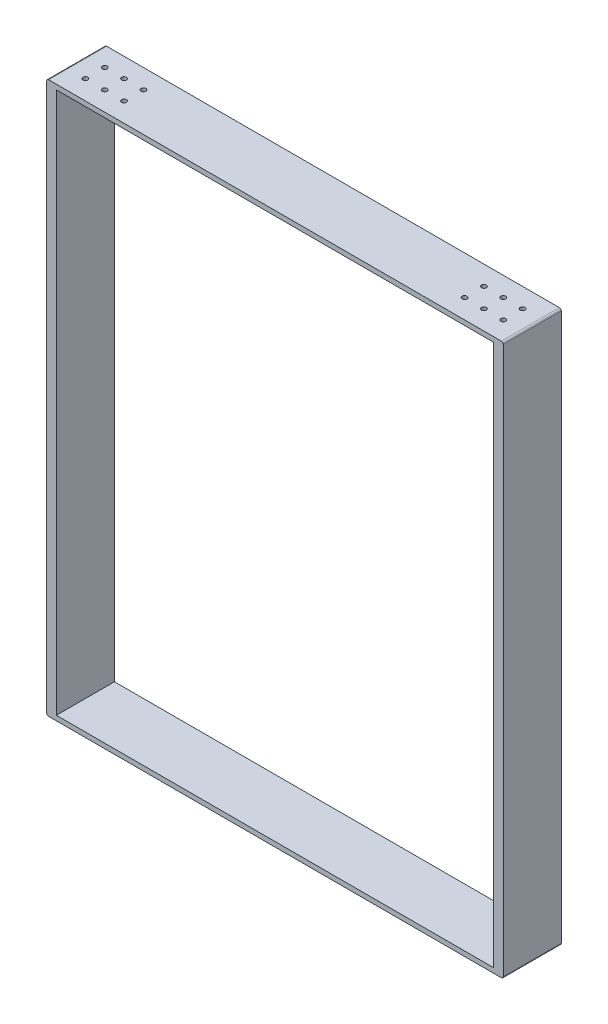
SolidWorks part; units mm, degrees
ref_plane "Front Plane" through (0, 0, 0) normal (0, 0, 1) x (1, 0, 0)
ref_plane "Top Plane" through (0, 0, 0) normal (0, 1, 0) x (1, 0, 0)
ref_plane "Right Plane" through (0, 0, 0) normal (1, 0, 0) x (0, 0, -1)
sketch "Sketch1" plane through (0, 0, 0) normal (0, 0, 1) x (1, 0, 0)
  line L0 (-287.02, 355.6) -> (-287.02, -355.6)
  line L1 (-287.02, -355.6) -> (287.02, -355.6)
  line L2 (287.02, -355.6) -> (287.02, 355.6)
  line L3 (287.02, 355.6) -> (-287.02, 355.6)
  line L4 (-299.72, 361.95) -> (-299.72, -361.95)
  line L5 (-299.72, -361.95) -> (299.72, -361.95)
  line L6 (299.72, -361.95) -> (299.72, 361.95)
  line L7 (299.72, 361.95) -> (-299.72, 361.95)
  line L8 (0, 355.6) -> (0, -355.6) construction
  line L9 (-287.02, 0) -> (287.02, 0) construction
  point P12 (0, 0)
  dimension "D1" = 12.7
  dimension "D2" = 12.7
  dimension "D3" = 6.35
  dimension "D4" = 6.35
  dimension "D5" = 599.44
  dimension "D6" = 723.9
extrude "Boss-Extrude1" add sketch "Sketch1" along normal blind 76.2
sketch "Sketch2" plane through (0, 361.95, 0) normal (0, 1, 0) x (1, 0, 0)
  line L0 (-299.72, -76.2) -> (-299.72, 0) construction
  circle A0 centre (-274.32, -50.8) radius 3.175
  circle A1 centre (-274.32, -25.4) radius 3.175
  circle A2 centre (-248.92, -50.8) radius 3.175
  circle A3 centre (-248.92, -25.4) radius 3.175
  circle A4 centre (-223.52, -50.8) radius 3.175
  circle A5 centre (-223.52, -25.4) radius 3.175
  dimension "D1" = 6.35
  dimension "D2" = 25.4
  dimension "D3" = 25.4
  dimension "D4" = 2
  dimension "D5" = 3
extrude "Cut-Extrude1" cut sketch "Sketch2" against normal up to next
mirror "Mirror1" about plane through (0, 0, 0) normal (1, 0, 0) of "Cut-Extrude1"
fillet "Fillet1" radius 2.54 4 edges at (-299.72, -361.95, 38.1) (299.72, -361.95, 38.1) (299.72, 361.95, 38.1) (-299.72, 361.95, 38.1)
